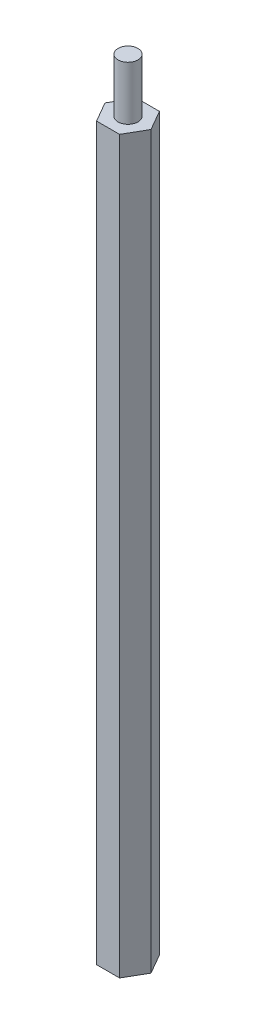
SolidWorks part; units mm, degrees
ref_plane "Front Plane" through (0, 0, 0) normal (0, 0, 1) x (1, 0, 0)
ref_plane "Top Plane" through (0, 0, 0) normal (0, 1, 0) x (1, 0, 0)
ref_plane "Right Plane" through (0, 0, 0) normal (1, 0, 0) x (0, 0, -1)
sketch "Sketch3" plane through (0, 0, 0) normal (0, 1, 0) x (1, 0, 0)
  line L1 (-3.4641, 0) -> (-1.7321, -3)
  line L2 (-1.7321, -3) -> (1.7321, -3)
  line L3 (1.7321, -3) -> (3.4641, 0)
  line L4 (3.4641, 0) -> (1.7321, 3)
  line L5 (1.7321, 3) -> (-1.7321, 3)
  line L6 (-1.7321, 3) -> (-3.4641, 0)
  circle A0 centre (0, 0) radius 3 construction
  dimension "D1" = 6
extrude "Boss-Extrude1" add sketch "Sketch3" along normal blind 110
sketch "Sketch5" plane through (0, 110, 0) normal (0, 1, 0) x (1, 0, 0)
  circle A0 centre (0, 0) radius 1.5
  dimension "D1" = 3
extrude "Boss-Extrude2" add sketch "Sketch5" along normal blind 8.0916
sketch "Sketch6" plane through (0, 0, 0) normal (0, -1, 0) x (1, 0, 0)
  circle A0 centre (0, 0) radius 1.5
extrude "Cut-Extrude1" cut sketch "Sketch6" against normal blind 4
